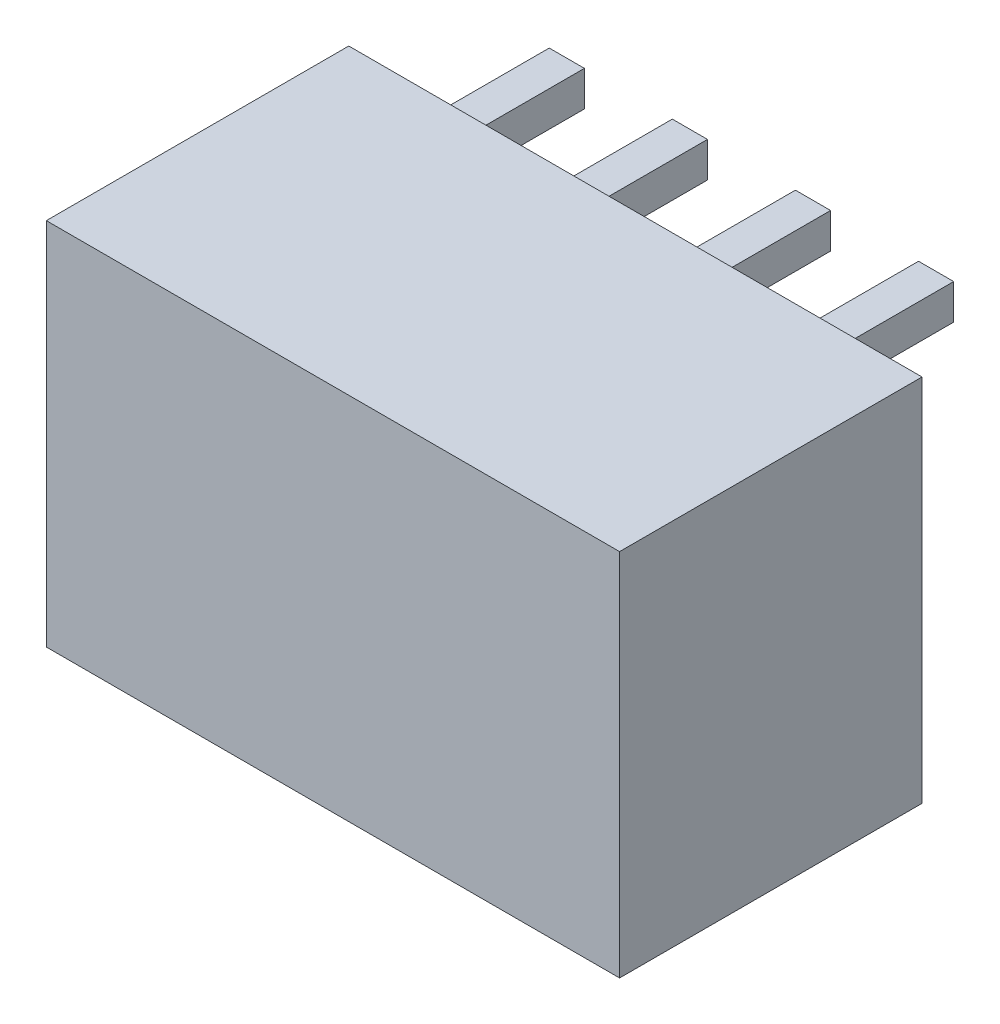
SolidWorks part; units mm, degrees
ref_plane "Спереди" through (0, 0, 0) normal (0, 0, 1) x (1, 0, 0)
ref_plane "Сверху" through (0, 0, 0) normal (0, 1, 0) x (1, 0, 0)
ref_plane "Справа" through (0, 0, 0) normal (1, 0, 0) x (0, 0, -1)
sketch "Эскиз1" plane through (0, 0, 0) normal (0, 0, 1) x (1, 0, 0)
  line L1 (-8.15, -5.25) -> (8.15, -5.25)
  line L2 (-8.15, -5.25) -> (-8.15, 5.25)
  line L3 (-8.15, 5.25) -> (8.15, 5.25)
  line L4 (8.15, -5.25) -> (8.15, 5.25)
  line L5 (-8.15, -5.25) -> (8.15, 5.25) construction
  line L6 (-8.15, 5.25) -> (8.15, -5.25) construction
  point P0 (0, 0)
  dimension "D1" = 16.3
  dimension "D2" = 10.5
extrude "Бобышка-Вытянуть1" add sketch "Эскиз1" along normal blind 8.6
sketch "Эскиз2" plane through (0, -5.25, 0) normal (0, -1, 0) x (1, 0, 0)
  line L0 (-7.15, 6.6) -> (7.15, 6.6)
  line L1 (7.15, 6.6) -> (7.15, 0.2)
  line L2 (7.15, 0.2) -> (4.95, 0.2)
  line L3 (4.95, 0.2) -> (4.95, 1.8)
  line L4 (4.95, 1.8) -> (-3.35, 1.8)
  line L5 (-3.35, 1.8) -> (-3.35, 0.2)
  line L6 (-3.35, 0.2) -> (-5.55, 0.2)
  line L7 (-7.15, 6.6) -> (-7.15, 1.8)
  line L8 (-7.15, 1.8) -> (-5.55, 1.8)
  line L9 (-5.55, 1.8) -> (-5.55, 0.2)
  line L10 (8.15, 8.6) -> (8.15, 0) construction
  line L11 (-8.15, 8.6) -> (-8.15, 0) construction
  line L12 (-8.15, 8.6) -> (8.15, 8.6) construction
  dimension "D1" = 4.8
  dimension "D2" = 6.4
  dimension "D3" = 2.2
  dimension "D4" = 2.2
  dimension "D5" = 3.2
  dimension "D6" = 4.8
  dimension "D7" = 1
  dimension "D8" = 2
extrude "Вырез-Вытянуть1" cut sketch "Эскиз2" against normal blind 7
sketch "Эскиз3" plane through (0, 0, 0) normal (0, 0, -1) x (-1, 0, 0)
  line L0 (8.15, -5.25) -> (-8.15, -5.25) construction
  line L1 (5.75, 4.75) -> (4.75, 4.75)
  line L2 (5.75, 4.75) -> (5.75, 3.75)
  line L3 (5.75, 3.75) -> (4.75, 3.75)
  line L4 (4.75, 4.75) -> (4.75, 3.75)
  line L5 (5.75, 4.75) -> (4.75, 3.75) construction
  line L6 (5.75, 3.75) -> (4.75, 4.75) construction
  line L7 (8.15, 5.25) -> (8.15, -5.25) construction
  point P0 (5.25, 4.25)
  dimension "D1" = 1
  dimension "D2" = 9.5
  dimension "D3" = 2.9
extrude "Бобышка-Вытянуть2" add sketch "Эскиз3" along normal blind 3.6 and the other way blind 5
chamfer "Фаска1" distance 0.3 distance2 0.3 4 edges at (-4.75, 4.25, -3.6) (-5.25, 3.75, -3.6) (-5.75, 4.25, -3.6) (-5.25, 4.75, -3.6)
pattern_linear "Линейный массив1" count 4 spacing 3.5 along (1, 0, 0) of "Бобышка-Вытянуть2", "Фаска1"
equation "\"N\"= 4"
equation "\"D1@Эскиз1\"= ( \"N\" - 1 ) * 3.5 + 5.8"
equation "\"D1@Линейный массив1\"=\"N\""
